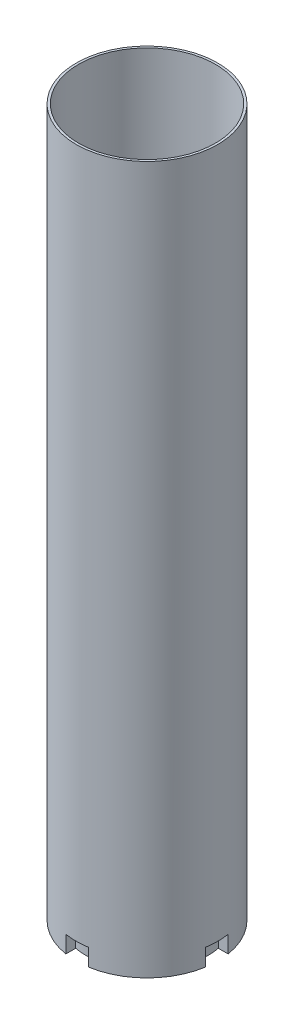
SolidWorks part; units mm, degrees
material "PBT General Purpose"
ref_plane "Front Plane" through (0, 0, 0) normal (0, 0, 1) x (1, 0, 0)
ref_plane "Top Plane" through (0, 0, 0) normal (0, 1, 0) x (1, 0, 0)
ref_plane "Right Plane" through (0, 0, 0) normal (1, 0, 0) x (0, 0, -1)
sketch "Sketch1" plane through (0, 0, 0) normal (0, 1, 0) x (1, 0, 0)
  circle A0 centre (0, 0) radius 31
extrude "Boss-Extrude1" add sketch "Sketch1" along normal blind 310
sketch "Sketch2" plane through (0, 310, 0) normal (0, 1, 0) x (1, 0, 0)
  circle A0 centre (0, 0) radius 30
extrude "Cut-Extrude1" cut sketch "Sketch2" against normal blind 300
sketch "Sketch3" plane through (0, 0, 0) normal (0, -1, 0) x (1, 0, 0)
  line L0 (-26.2786, -5) -> (-30.5941, -5)
  line L1 (-26.2786, 5) -> (-30.5941, 5)
  line L2 (-5, -26.2786) -> (-5, -30.5941)
  line L3 (-5, 26.2786) -> (-5, 30.5941)
  line L4 (5, -26.2786) -> (5, -30.5941)
  line L5 (5, 26.2786) -> (5, 30.5941)
  line L6 (26.2786, 5) -> (30.5941, 5)
  line L7 (26.2786, -5) -> (30.5941, -5)
  circle A0 centre (0, 0) radius 31 construction
  arc A1 (-5, -30.5941) -> (5, -30.5941) centre (0, 0) ccw
  arc A2 (-5, -26.2786) -> (5, -26.2786) centre (0, 0) ccw
  arc A3 (-30.5941, 5) -> (-30.5941, -5) centre (0, 0) ccw
  arc A4 (-26.2786, 5) -> (-26.2786, -5) centre (0, 0) ccw
  arc A5 (5, 30.5941) -> (-5, 30.5941) centre (0, 0) ccw
  arc A6 (5, 26.2786) -> (-5, 26.2786) centre (0, 0) ccw
  arc A7 (30.5941, -5) -> (30.5941, 5) centre (0, 0) ccw
  arc A8 (26.2786, -5) -> (26.2786, 5) centre (0, 0) ccw
  dimension "D1" = 4
extrude "Cut-Extrude2" cut sketch "Sketch3" against normal blind 7.5
